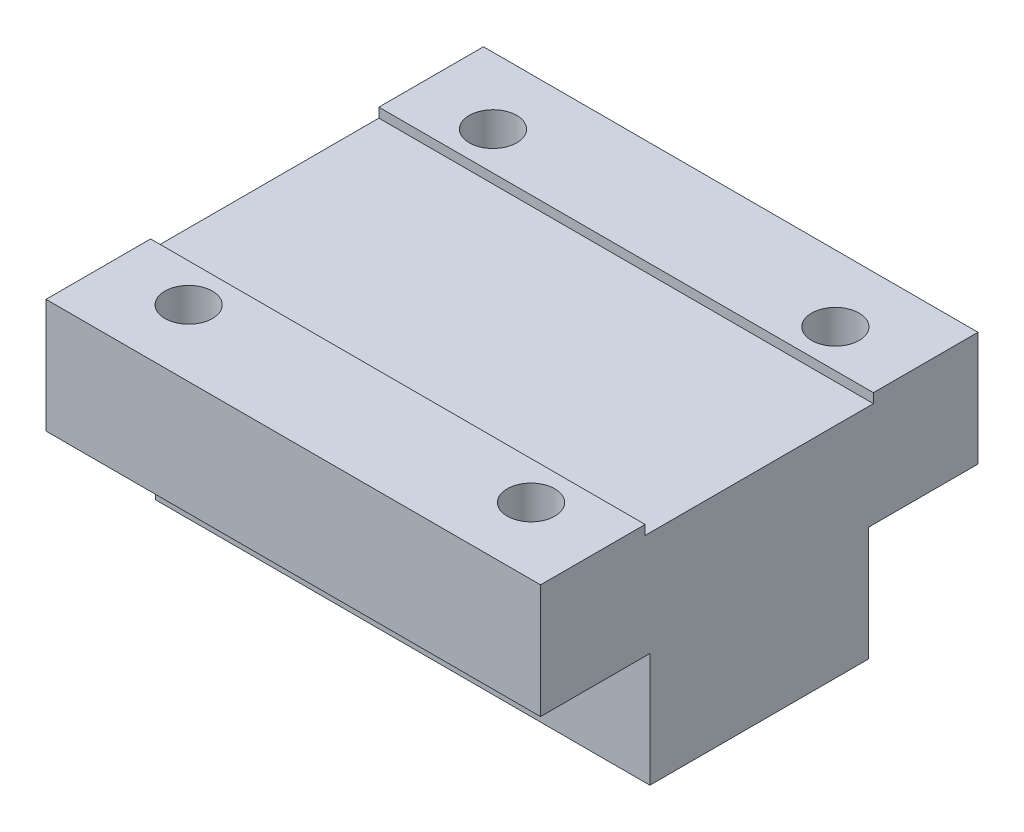
SolidWorks part; units mm, degrees
ref_plane "前视基准面" through (0, 0, 0) normal (0, 0, 1) x (1, 0, 0)
ref_plane "上视基准面" through (0, 0, 0) normal (0, 1, 0) x (1, 0, 0)
ref_plane "右视基准面" through (0, 0, 0) normal (1, 0, 0) x (0, 0, -1)
sketch "草图1" plane through (0, 0, 0) normal (0, 1, 0) x (1, 0, 0)
  line L1 (0, 0) -> (52, 0)
  line L2 (0, 0) -> (0, 46)
  line L3 (0, 46) -> (52, 46)
  line L4 (52, 0) -> (52, 46)
  dimension "D1" = 46
  dimension "D2" = 52
extrude "凸台-拉伸1" add sketch "草图1" along normal blind 12
sketch "草图2" plane through (0, 0, 0) normal (0, -1, 0) x (1, 0, 0)
  line L0 (0, -46) -> (0, 0) construction
  line L1 (0, -34.5) -> (52, -34.5)
  line L2 (0, -34.5) -> (0, -11.5)
  line L3 (0, -11.5) -> (52, -11.5)
  line L4 (52, -34.5) -> (52, -11.5)
  line L5 (52, 0) -> (52, -46) construction
  point P8 (0, -23)
  point P9 (0, -23)
  dimension "D1" = 23
extrude "凸台-拉伸2" add sketch "草图2" along normal blind 12
sketch "草图3" plane through (0, 12, 0) normal (0, 1, 0) x (1, 0, 0)
  line L0 (26, 46) -> (26, 0) construction
  line L1 (52, 46) -> (0, 46) construction
  line L2 (0, 0) -> (52, 0) construction
  line L3 (0, 23) -> (52, 23) construction
  line L4 (0, 46) -> (0, 0) construction
  line L5 (52, 0) -> (52, 46) construction
  circle A0 centre (8, 39) radius 2.5
  circle A1 centre (8, 7) radius 2.5
  circle A2 centre (44, 7) radius 2.5
  circle A3 centre (44, 39) radius 2.5
  dimension "D1" = 5
  dimension "D2" = 32
  dimension "D3" = 36
extrude "切除-拉伸1" cut sketch "草图3" against normal through all
cosmetic thread "装饰螺纹线1" parameters "D2"=6
cosmetic thread "装饰螺纹线2" parameters "D2"=6
cosmetic thread "装饰螺纹线3" parameters "D2"=6
cosmetic thread "装饰螺纹线4" parameters "D2"=6
sketch "草图4" plane through (0, 0, 0) normal (-1, 0, 0) x (0, 0, 1)
  line L0 (-35, 11) -> (-35, 12)
  line L1 (-35, 11) -> (-11, 11)
  line L2 (-35, 12) -> (-11, 12)
  line L3 (-11, 11) -> (-11, 12)
  line L4 (-35, 11) -> (-11, 12) construction
  line L5 (-35, 12) -> (-11, 11) construction
  line L6 (-46, 12) -> (0, 12) construction
  point P0 (-23, 12)
  point P1 (-23, 11.5)
  point P2 (-23, 12)
  dimension "D1" = 24
  dimension "D2" = 1
extrude "切除-拉伸2" cut sketch "草图4" against normal through all
